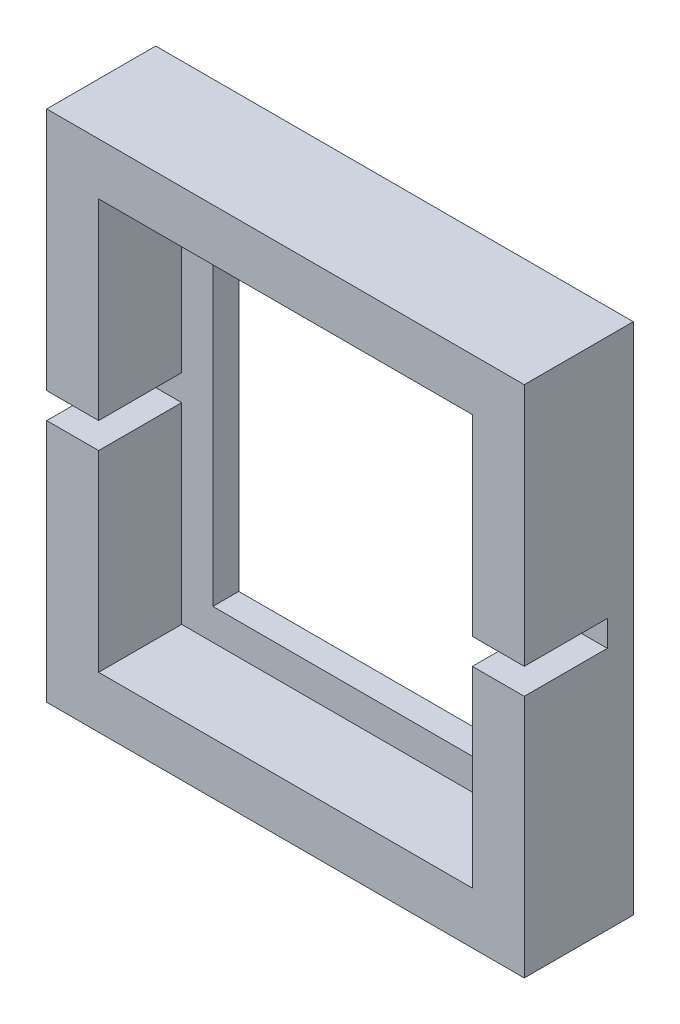
SolidWorks part; units mm, degrees
ref_plane "Front Plane" through (0, 0, 0) normal (0, 0, 1) x (1, 0, 0)
ref_plane "Top Plane" through (0, 0, 0) normal (0, 1, 0) x (1, 0, 0)
ref_plane "Right Plane" through (0, 0, 0) normal (1, 0, 0) x (0, 0, -1)
sketch "Sketch1" plane through (0, 0, 0) normal (0, 0, 1) x (1, 0, 0)
  line L0 (0, 39.5) -> (-5, 44.5) construction
  line L1 (0, 0) -> (36, 0)
  line L2 (0, 0) -> (0, 39.5)
  line L3 (0, 39.5) -> (36, 39.5)
  line L4 (36, 0) -> (36, 39.5)
  line L5 (-5, 44.5) -> (41, 44.5)
  line L6 (-5, 44.5) -> (-5, -5)
  line L7 (-5, -5) -> (41, -5)
  line L8 (41, 44.5) -> (41, -5)
  line L9 (0, 0) -> (-5, -5) construction
  line L10 (36, 0) -> (41, -5) construction
  line L11 (36, 39.5) -> (41, 44.5) construction
  line L12 (-5, 21) -> (0, 39.5) construction
  line L13 (-5, 21) -> (0, 21)
  line L14 (-5, 21) -> (-5, 18.5)
  line L15 (-5, 18.5) -> (0, 18.5)
  line L16 (0, 21) -> (0, 18.5)
  line L17 (-5, 18.5) -> (0, 0) construction
  line L18 (18, 44.5) -> (18, -5) construction
  line L19 (36, 21) -> (36, 18.5)
  line L20 (41, 18.5) -> (36, 18.5)
  line L21 (41, 21) -> (41, 18.5)
  line L22 (41, 21) -> (36, 21)
  dimension "D1" = 36
  dimension "D2" = 39.5
  dimension "D3" = 49.5
  dimension "D4" = 46
  dimension "D5" = 2.5
extrude "Boss-Extrude1" add sketch "Sketch1" along normal blind 8 contours L22 L8 L5 L6 L13 L2 L3 L4 | L8 L20 L4 L1 L2 L15 L6 L7
sketch "Sketch2" plane through (0, 0, 0) normal (0, 0, -1) x (-1, 0, 0)
  line L0 (-36, 39.5) -> (-33, 36.5) construction
  line L1 (-41, 44.5) -> (5, 44.5)
  line L2 (-41, 44.5) -> (-41, -5)
  line L3 (-41, -5) -> (5, -5)
  line L4 (5, 44.5) -> (5, -5)
  line L5 (-33, 36.5) -> (-3, 36.5)
  line L6 (-33, 36.5) -> (-33, 3)
  line L7 (-33, 3) -> (-3, 3)
  line L8 (-3, 36.5) -> (-3, 3)
  line L9 (-3, 36.5) -> (0, 39.5) construction
  line L10 (-36, 0) -> (-33, 3) construction
  line L11 (0, 0) -> (-3, 3) construction
  dimension "D1" = 30
  dimension "D2" = 33.5
extrude "Boss-Extrude2" add sketch "Sketch2" along normal blind 2.5
